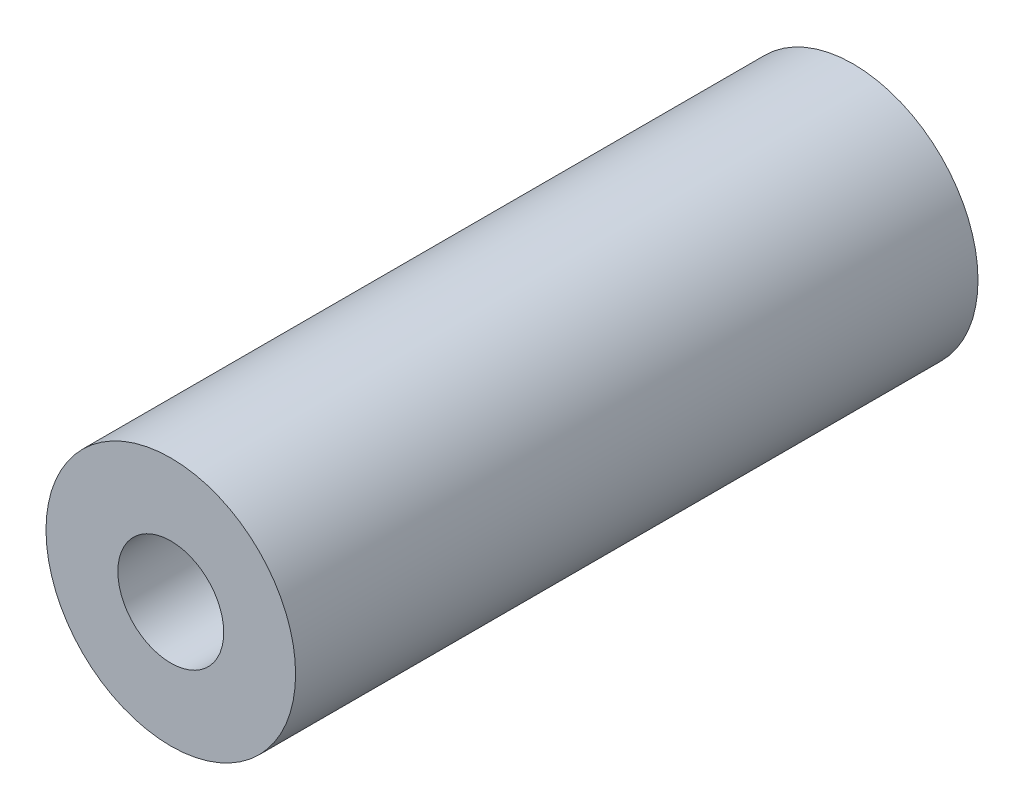
SolidWorks part; units mm, degrees
material "6061-T6 (SS)"
ref_plane "Front Plane" through (0, 0, 0) normal (0, 0, 1) x (1, 0, 0)
ref_plane "Top Plane" through (0, 0, 0) normal (0, 1, 0) x (1, 0, 0)
ref_plane "Right Plane" through (0, 0, 0) normal (1, 0, 0) x (0, 0, -1)
sketch "Sketch1" plane through (0, 0, 0) normal (0, 0, 1) x (1, 0, 0)
  circle A0 centre (0, 0) radius 4.7625
  dimension "D1" = 9.525
extrude "Boss-Extrude1" add sketch "Sketch1" along normal mid plane 26.0426
hole_wizard "#10-32 Tapped Hole2" positions "3DSketch1" profile "Sketch4" tap size "#10-32" standard "ANSI Inch"
sketch3d "3DSketch1"
  line L0 (0, 0, 13.0213) -> (0, 0, -13.0213) construction
  point P0 (0, 0, 13.0213)
  point P4 (0, 0, -13.0213)
sketch "Sketch4" plane through (0, 0, 13.0213) normal (1, 0, 0) x (0, -1, 0)
  line L0 (0, 0) -> (0, 16.2908)
  line L1 (0, 16.2908) -> (2.0193, 15.0774)
  line L2 (2.0193, 15.0774) -> (2.0193, 0)
  line L5 (2.0193, 0) -> (0, 0)
  line L10 (0, 16.2908) -> (-2.0193, 15.0774) construction
  line L11 (0, -6.35) -> (0, 107.95) construction
  dimension "Tap Drill Dia." = 4.0386
  dimension "Tap Drill Depth" = 15.0774
  dimension "Drill Angle" = 118
cosmetic thread "Hole Thread2" parameters "D1"=12.7, "D2"=4.826
cosmetic thread "Hole Thread3" parameters "D1"=12.7, "D2"=4.826
